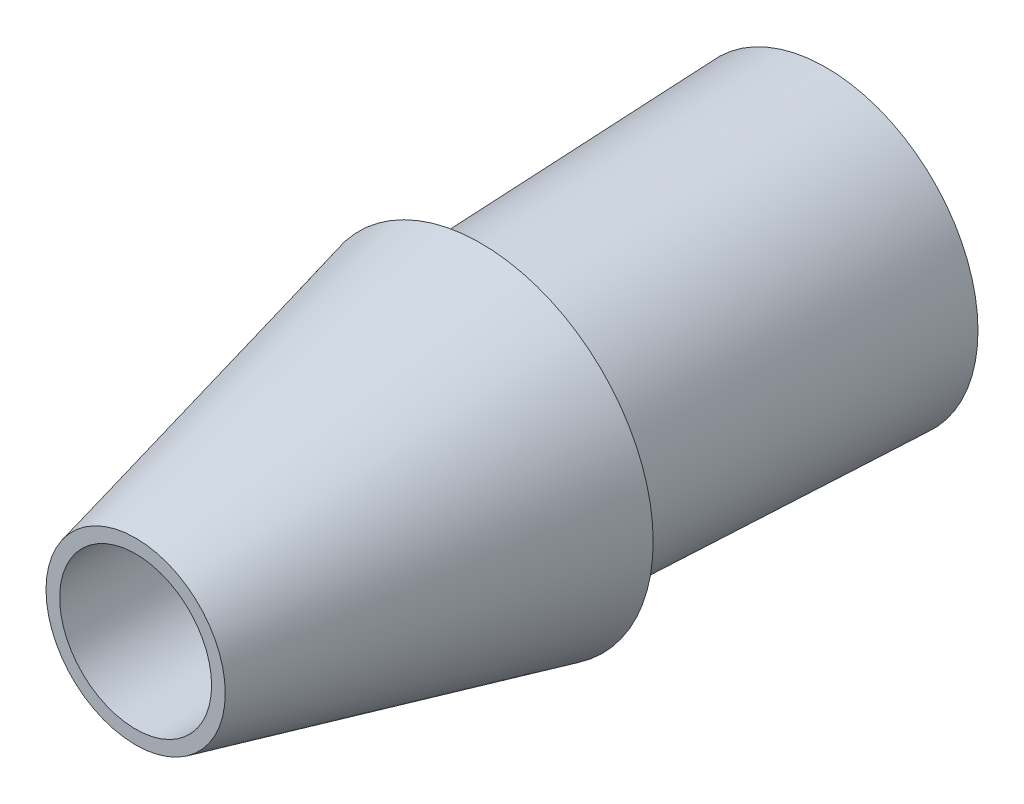
SolidWorks part; units mm, degrees
ref_plane "Front Plane" through (0, 0, 0) normal (0, 0, 1) x (1, 0, 0)
ref_plane "Top Plane" through (0, 0, 0) normal (0, 1, 0) x (1, 0, 0)
ref_plane "Right Plane" through (0, 0, 0) normal (1, 0, 0) x (0, 0, -1)
sketch "Sketch1" plane through (0, 0, 0) normal (0, 0, 1) x (1, 0, 0)
  circle A0 centre (0, 0) radius 1.1
ref_plane "Plane1" through (0, 0, 2.5) normal (0, 0, 1) x (1, 0, 0)
sketch "Sketch2" plane through (0, 0, 2.5) normal (0, 0, 1) x (1, 0, 0)
  circle A0 centre (0, 0) radius 1.0038
loft "Loft1" add profiles "Sketch1", "Sketch2"
sketch "Sketch3" plane through (0, 0, 2.5) normal (0, 0, 1) x (1, 0, 0)
  circle A0 centre (0, 0) radius 0.9036
extrude "Cut-Extrude1" cut sketch "Sketch3" against normal blind 10
sketch "Sketch4" plane through (0, 0, 2.5) normal (0, 0, 1) x (1, 0, 0)
  circle A0 centre (0, 0) radius 1.2479
ref_plane "Plane2" through (0, 0, 5) normal (0, 0, 1) x (1, 0, 0)
sketch "Sketch5" plane through (0, 0, 5) normal (0, 0, 1) x (1, 0, 0)
  circle A0 centre (0, 0) radius 0.649
loft "Loft2" add profiles "Sketch4", "Sketch5"
sketch "Sketch6" plane through (0, 0, 5) normal (0, 0, 1) x (1, 0, 0)
  circle A0 centre (0, 0) radius 0.55
extrude "Cut-Extrude2" cut sketch "Sketch6" against normal blind 10
